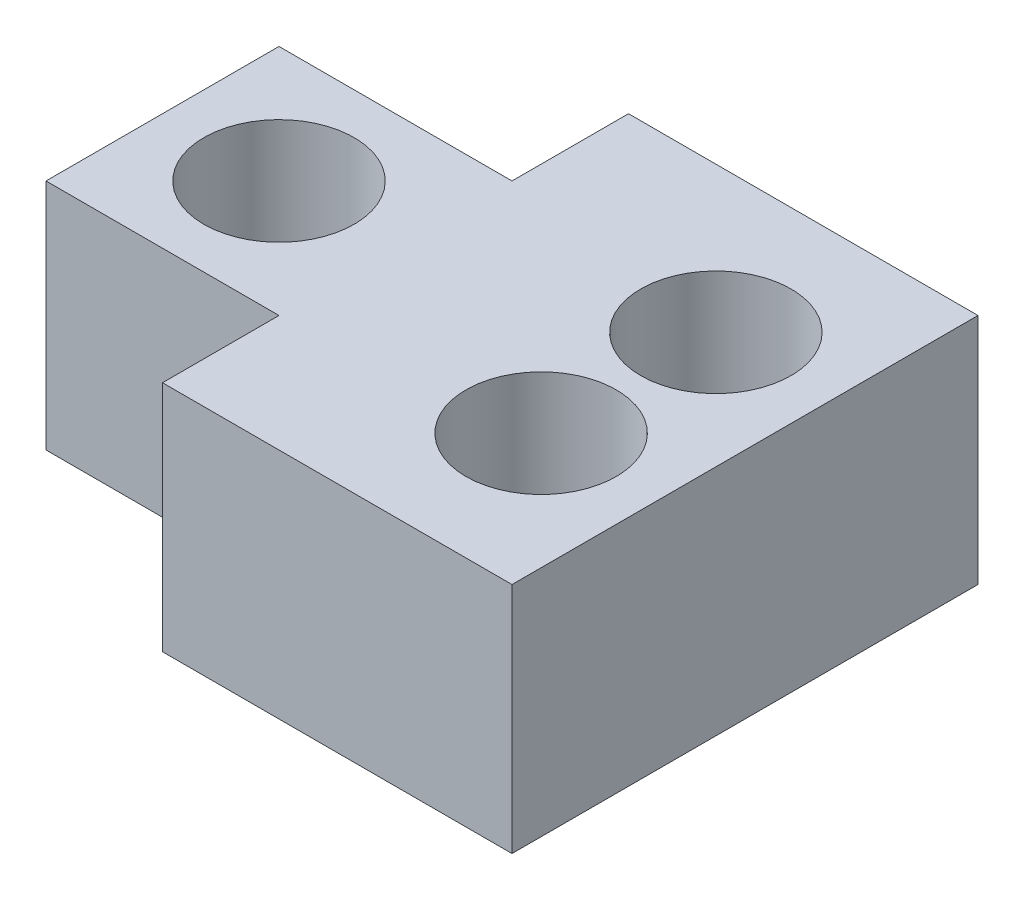
SolidWorks part; units mm, degrees
ref_plane "Front Plane" through (0, 0, 0) normal (0, 0, 1) x (1, 0, 0)
ref_plane "Top Plane" through (0, 0, 0) normal (0, 1, 0) x (1, 0, 0)
ref_plane "Right Plane" through (0, 0, 0) normal (1, 0, 0) x (0, 0, -1)
sketch "Sketch1" plane through (0, 0, 0) normal (0, 1, 0) x (1, 0, 0)
  line L1 (-33.0565, 8.9136) -> (-13.0565, 8.9136)
  line L2 (-33.0565, 8.9136) -> (-33.0565, -11.0864)
  line L3 (-33.0565, -11.0864) -> (-13.0565, -11.0864)
  line L4 (-13.0565, 8.9136) -> (-13.0565, -11.0864)
  line L5 (-13.0565, 18.9136) -> (16.9435, 18.9136)
  line L6 (-13.0565, 18.9136) -> (-13.0565, -21.0864)
  line L7 (-13.0565, -21.0864) -> (16.9435, -21.0864)
  line L8 (16.9435, 18.9136) -> (16.9435, -21.0864)
  circle A0 centre (-23.0565, -1.0864) radius 6.45
  circle A1 centre (6.9435, 6.4136) radius 6.45
  circle A2 centre (6.9435, -8.5864) radius 6.45
  dimension "D1" = 20
  dimension "D2" = 12.9
  dimension "D6" = 12.9
  dimension "D7" = 12.9
  dimension "D8" = 15
  dimension "D3" = 20
  dimension "D4" = 10
  dimension "D5" = 10
  dimension "D9" = 30
  dimension "D10" = 7.5
  dimension "D11" = 0
  dimension "D12" = 20
  dimension "D14" = 20
  dimension "D15" = 30
  dimension "D16" = 20
extrude "Boss-Extrude1" add sketch "Sketch1" along normal blind 20 contours L8 L5 L6 L4 L7 A2 A1 | L4 L1 L2 L3 A0
